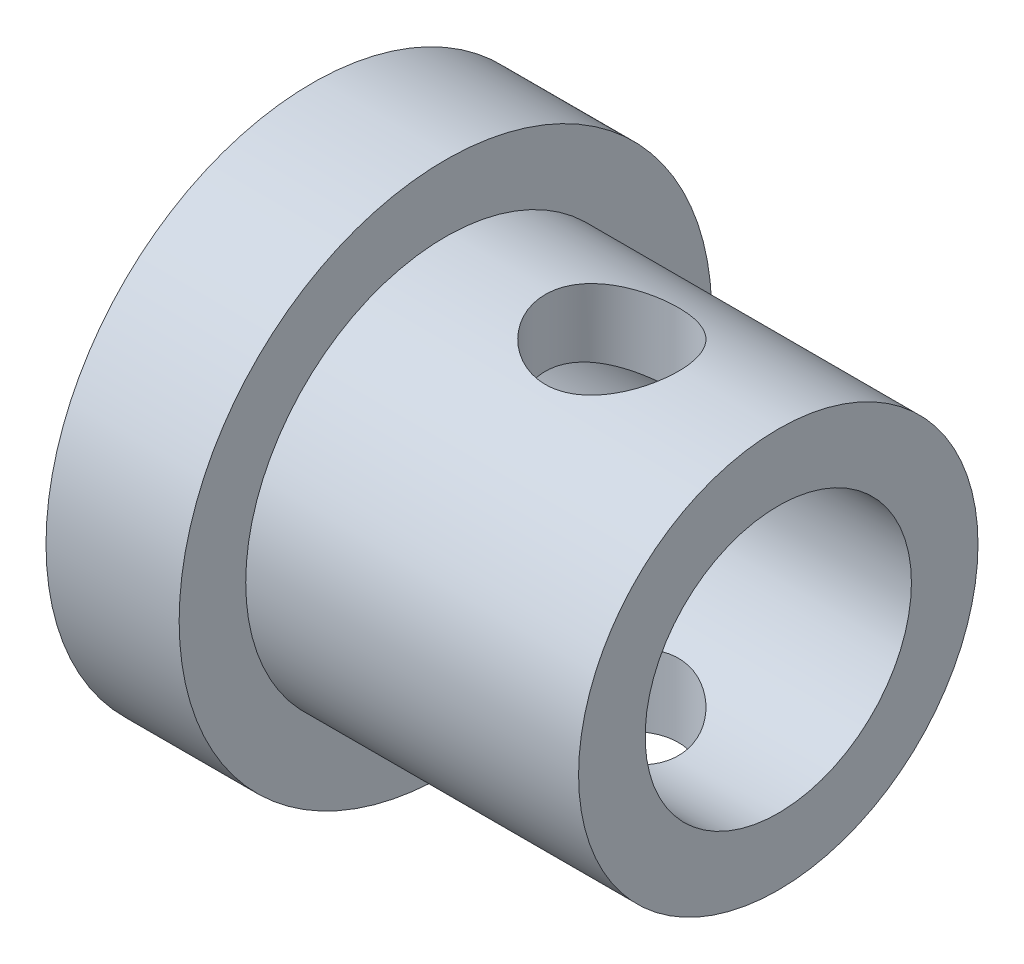
SolidWorks part; units mm, degrees
ref_plane "Front Plane" through (0, 0, 0) normal (0, 0, 1) x (1, 0, 0)
ref_plane "Top Plane" through (0, 0, 0) normal (0, 1, 0) x (1, 0, 0)
ref_plane "Right Plane" through (0, 0, 0) normal (1, 0, 0) x (0, 0, -1)
sketch "Sketch1" plane through (0, 0, 0) normal (1, 0, 0) x (0, 0, -1)
  circle A0 centre (0, 0) radius 3
  dimension "D1" = 6
extrude "Boss-Extrude1" add sketch "Sketch1" along normal mid plane 7
sketch "Sketch2" plane through (-3.5, 0, 0) normal (-1, 0, 0) x (0, 0, 1)
  circle A0 centre (0, 0) radius 4
  dimension "D1" = 8
extrude "Boss-Extrude2" add sketch "Sketch2" against normal blind 2
sketch "Sketch3" plane through (3.5, 0, 0) normal (1, 0, 0) x (0, 0, -1)
  circle A0 centre (0, 0) radius 2
  dimension "D1" = 4
extrude "Cut-Extrude1" cut sketch "Sketch3" against normal through all
sketch "Sketch4" plane through (0, 0, 0) normal (0, 1, 0) x (1, 0, 0)
  line L0 (3.5, -3) -> (3.5, 3) construction
  circle A0 centre (1, 0) radius 1
  dimension "D1" = 2
  dimension "D2" = 2.5
extrude "Cut-Extrude2" cut sketch "Sketch4" against normal through all both and the other way through all
